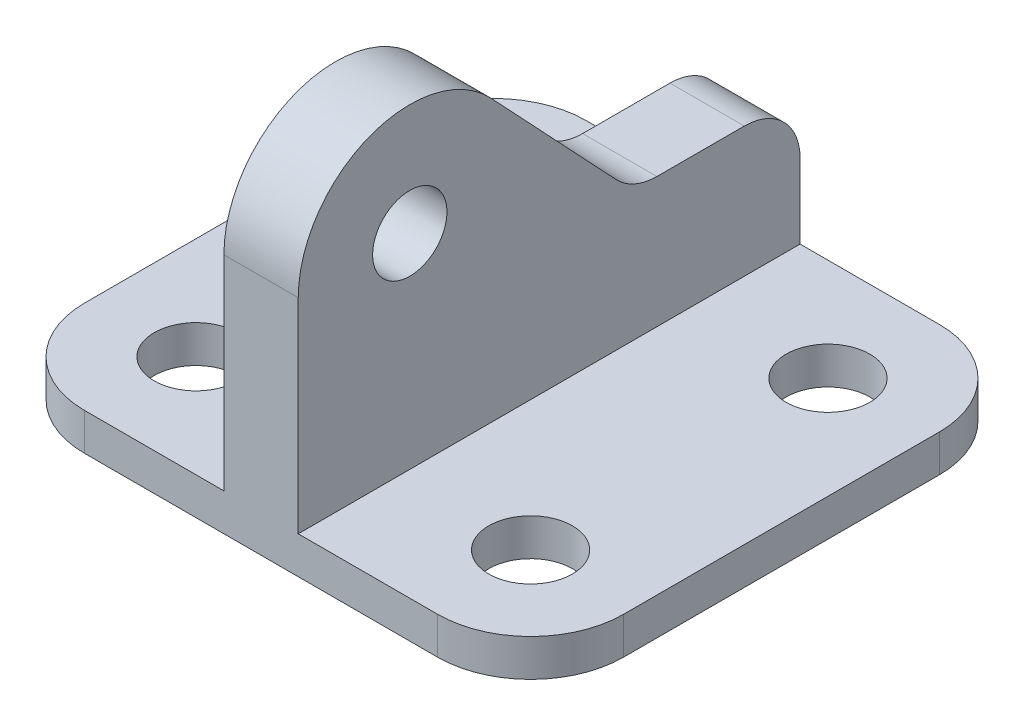
SolidWorks part; units mm, degrees
material "Acier non allié"
ref_plane "Plan de face" through (0, 0, 0) normal (0, 0, 1) x (1, 0, 0)
ref_plane "Plan de dessus" through (0, 0, 0) normal (0, 1, 0) x (1, 0, 0)
ref_plane "Plan de droite" through (0, 0, 0) normal (1, 0, 0) x (0, 0, -1)
sketch "Esquisse1" plane through (0, 0, 0) normal (0, 0, 1) x (1, 0, 0)
  line L0 (0, 0) -> (29, 0)
  line L1 (29, 0) -> (29, 2)
  line L2 (29, 2) -> (16.5, 2)
  line L3 (16.5, 2) -> (16.5, 19)
  line L4 (16.5, 19) -> (12.5, 19)
  line L5 (12.5, 19) -> (12.5, 2)
  line L6 (12.5, 2) -> (0, 2)
  line L7 (0, 2) -> (0, 0)
  dimension "D1" = 29
  dimension "D2" = 2
  dimension "D3" = 4
  dimension "D4" = 19
extrude "Boss.-Extru.1" add sketch "Esquisse1" along normal blind 27
fillet "Congé1" radius 5 4 edges at (0, 1, 0) (29, 1, 0) (29, 1, 27) (0, 1, 27)
sketch "Esquisse2" plane through (0, 0, 0) normal (0, -1, 0) x (1, 0, 0)
  line L0 (14.5, 0) -> (14.5, 5.5) construction
  line L1 (23.5, 5.5) -> (5.5, 5.5) construction
  line L2 (23.5, 5.5) -> (23.5, 21.5) construction
  line L3 (23.5, 21.5) -> (5.5, 21.5) construction
  line L4 (5.5, 5.5) -> (5.5, 21.5) construction
  line L5 (5, 0) -> (24, 0) construction
  line L7 (5.5, 13.5) -> (0, 13.5) construction
  line L8 (0, 22) -> (0, 5) construction
  circle A0 centre (5.5, 21.5) radius 2.25
  circle A1 centre (5.5, 5.5) radius 2.25
  circle A2 centre (23.5, 5.5) radius 2.25
  circle A3 centre (23.5, 21.5) radius 2.25
  dimension "D3" = 4.5
  dimension "D1" = 18
  dimension "D2" = 16
extrude "Enlèv. mat.-Extru.1" cut sketch "Esquisse2" against normal through all
sketch "Esquisse3" plane through (12.5, 0, 0) normal (-1, 0, 0) x (0, 0, 1)
  line L0 (0, 9) -> (9, 9)
  line L1 (0, 19) -> (0, 2) construction
  line L2 (27, 19) -> (27, 2) construction
  line L3 (27, 19) -> (0, 19) construction
  line L4 (9, 9) -> (16.6297, 17.111)
  line L5 (0, 9) -> (0, 22.0347)
  line L6 (0, 22.0347) -> (29.8746, 22.0347)
  line L7 (29.8746, 22.0347) -> (29.8746, 13)
  line L8 (29.8746, 13) -> (27, 13)
  arc A0 (27, 13) -> (16.6297, 17.111) centre (21, 13) ccw
  dimension "D1" = 12
  dimension "D2" = 9
  dimension "D3" = 9
  dimension "D4" = 13.0347
  dimension "D5" = 2.8746
extrude "Enlèv. mat.-Extru.2" cut sketch "Esquisse3" against normal blind 27
fillet "Congé2" radius 3 2 edges at (14.5, 9, 9) (14.5, 9, 0)
sketch "Esquisse4" plane through (12.5, 0, 0) normal (-1, 0, 0) x (0, 0, 1)
  circle A0 centre (21, 13) radius 2
  dimension "D1" = 4
extrude "Enlèv. mat.-Extru.3" cut sketch "Esquisse4" against normal through all
